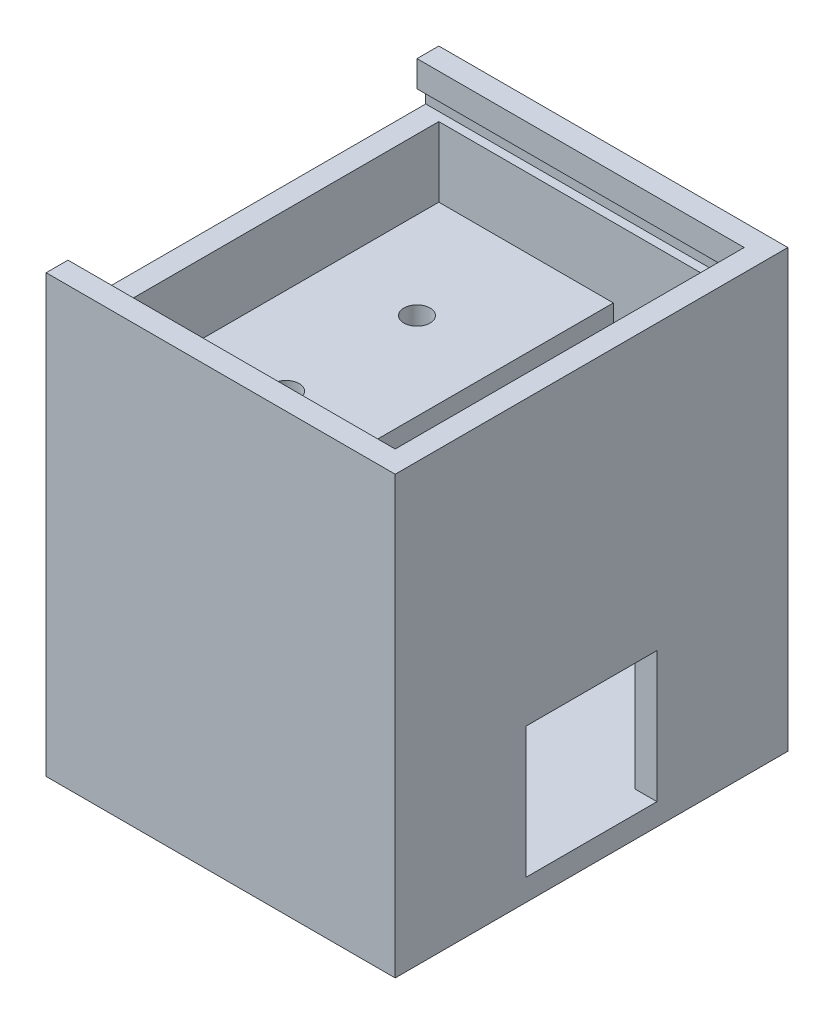
SolidWorks part; units mm, degrees
ref_plane "Front Plane" through (0, 0, 0) normal (0, 0, 1) x (1, 0, 0)
ref_plane "Top Plane" through (0, 0, 0) normal (0, 1, 0) x (1, 0, 0)
ref_plane "Right Plane" through (0, 0, 0) normal (1, 0, 0) x (0, 0, -1)
sketch "Sketch1" plane through (0, 0, 0) normal (0, 1, 0) x (1, 0, 0)
  line L1 (-34.8887, 14.0503) -> (5.1113, 14.0503)
  line L2 (-34.8887, 14.0503) -> (-34.8887, -30.9497)
  line L3 (-34.8887, -30.9497) -> (5.1113, -30.9497)
  line L4 (5.1113, 14.0503) -> (5.1113, -30.9497)
extrude "Boss-Extrude1" add sketch "Sketch1" along normal blind 50
shell "Shell1" thickness 2.5
sketch "Sketch3" plane through (-32.3887, 0, 0) normal (1, 0, 0) x (0, 0, -1)
  line L0 (-28.4497, 50) -> (-28.4497, 2.5) construction
  line L1 (11.5503, 2.5) -> (-28.4497, 2.5)
  line L2 (11.5503, 2.5) -> (11.5503, 37)
  line L3 (11.5503, 37) -> (-28.4497, 37)
  line L4 (-28.4497, 2.5) -> (-28.4497, 37)
extrude "Boss-Extrude2" add sketch "Sketch3" along normal blind 20
sketch "Sketch11" plane through (-32.3887, 0, 0) normal (1, 0, 0) x (0, 0, -1)
  line L0 (-28.4497, 50) -> (-28.4497, 37) construction
  line L1 (11.5503, 50) -> (-28.4497, 50)
  line L2 (11.5503, 50) -> (11.5503, 45)
  line L3 (11.5503, 45) -> (-28.4497, 45)
  line L4 (-28.4497, 50) -> (-28.4497, 45)
extrude "Cut-Extrude2" cut sketch "Sketch11" against normal blind 2.5
sketch "Sketch12" plane through (0, 0, -11.5503) normal (0, 0, 1) x (1, 0, 0)
  line L0 (2.6113, 50) -> (2.6113, 2.5) construction
  line L1 (-34.8887, 45) -> (2.6113, 45)
  line L2 (-34.8887, 45) -> (-34.8887, 47)
  line L3 (-34.8887, 47) -> (2.6113, 47)
  line L4 (2.6113, 45) -> (2.6113, 47)
sketch "Sketch13" plane through (0, 0, 28.4497) normal (0, 0, -1) x (-1, 0, 0)
  line L0 (-2.6113, 50) -> (-2.6113, 2.5) construction
  line L1 (34.8887, 45) -> (-2.6113, 45)
  line L2 (34.8887, 45) -> (34.8887, 47)
  line L3 (34.8887, 47) -> (-2.6113, 47)
  line L4 (-2.6113, 45) -> (-2.6113, 47)
extrude "Cut-Extrude3" cut sketch "Sketch12" against normal blind 1
extrude "Cut-Extrude4" cut sketch "Sketch13" against normal blind 1
sketch "Sketch14" plane through (0, 37, 0) normal (0, 1, 0) x (1, 0, 0)
  line L0 (-32.3887, -28.4497) -> (-12.3887, 11.5503)
  line L1 (-12.3887, -28.4497) -> (-32.3887, 11.5503)
  line L2 (-22.3887, -28.4497) -> (-22.3887, 11.5503)
  line L3 (-12.3887, -28.4497) -> (-32.3887, -28.4497) construction
  line L4 (-12.3887, 11.5503) -> (-32.3887, 11.5503) construction
  circle A0 centre (-22.3887, -8.4497) radius 7.5
  point P16 (-22.3887, -15.9497)
  point P17 (-22.3887, -0.9497)
sketch "Sketch15" plane through (0, 37, 0) normal (0, 1, 0) x (1, 0, 0)
  circle A0 centre (-22.3887, -15.9497) radius 1.5
sketch "Sketch16" plane through (0, 37, 0) normal (0, 1, 0) x (1, 0, 0)
  circle A0 centre (-22.3887, -0.9497) radius 1.5
extrude "Cut-Extrude7" cut sketch "Sketch15" against normal blind 37
extrude "Cut-Extrude8" cut sketch "Sketch16" against normal blind 37
sketch "Sketch17" plane through (0, 0, 0) normal (0, -1, 0) x (1, 0, 0)
  circle A0 centre (-22.3887, 15.9497) radius 3
  circle A1 centre (-22.3887, 0.9497) radius 3
extrude "Cut-Extrude9" cut sketch "Sketch17" against normal blind 5
sketch "Sketch18" plane through (2.6113, 0, 0) normal (-1, 0, 0) x (0, 0, 1)
  line L0 (28.4497, 2.5) -> (-11.5503, 2.5)
  circle A1 centre (8.4497, 2.5) radius 7.5
  point P4 (8.4497, 2.5)
  point P7 (15.9497, 2.5)
  point P8 (0.9497, 2.5)
  point P9 (14.3782, -129.1627)
sketch "Sketch19" plane through (2.6113, 0, 0) normal (-1, 0, 0) x (0, 0, 1)
  line L1 (15.9497, 2.5) -> (0.9497, 2.5)
  line L2 (15.9497, 2.5) -> (15.9497, 17.5)
  line L3 (15.9497, 17.5) -> (0.9497, 17.5)
  line L4 (0.9497, 2.5) -> (0.9497, 17.5)
extrude "Cut-Extrude10" cut sketch "Sketch19" against normal blind 2.5
